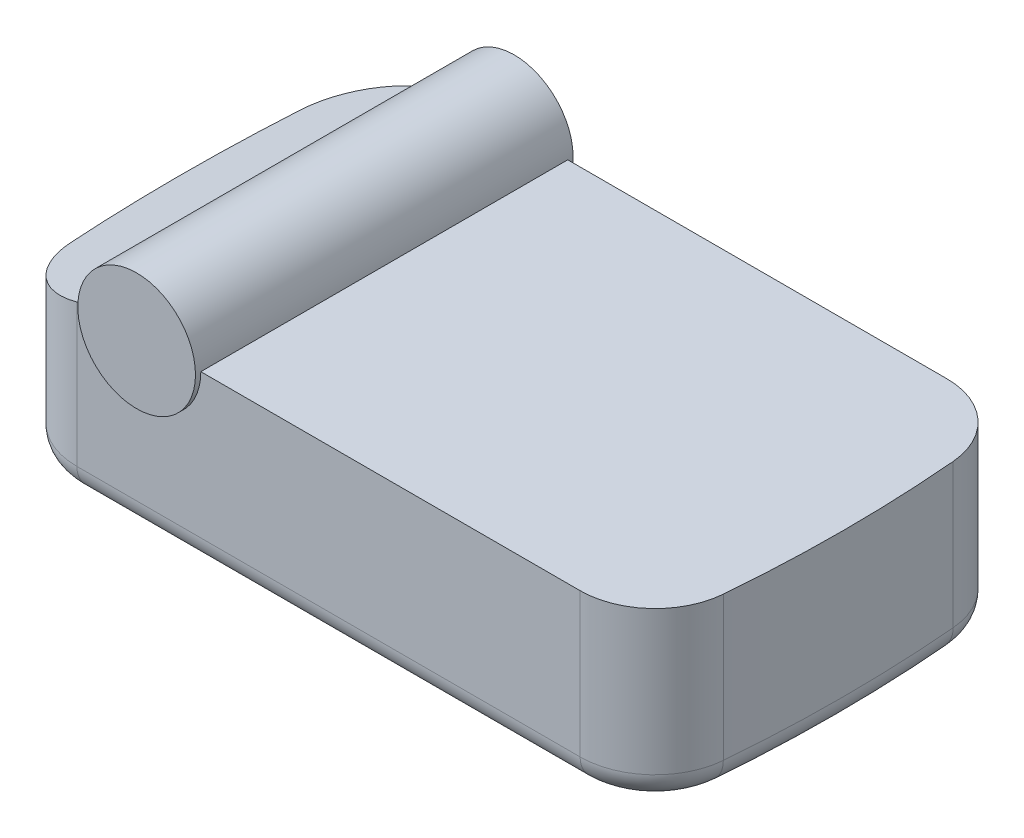
SolidWorks part; units mm, degrees
ref_plane "Front Plane" through (0, 0, 0) normal (0, 0, 1) x (1, 0, 0)
ref_plane "Top Plane" through (0, 0, 0) normal (0, 1, 0) x (1, 0, 0)
ref_plane "Right Plane" through (0, 0, 0) normal (1, 0, 0) x (0, 0, -1)
sketch "Sketch1" plane through (0, 0, 0) normal (0, 1, 0) x (1, 0, 0)
  line L0 (-29.7867, 17.15) -> (-29.7867, -17.15) construction
  line L1 (-23.52, 17.15) -> (23.52, 17.15)
  line L3 (-23.52, -17.15) -> (23.52, -17.15)
  line L5 (-29.7867, 17.15) -> (29.7867, -17.15) construction
  line L6 (-29.7867, -17.15) -> (29.7867, 17.15) construction
  line L7 (29.7867, 17.15) -> (29.7867, -17.15) construction
  arc A0 (-30.4949, 10.7421) -> (-30.4949, -10.7421) centre (96.05, 0) ccw
  arc A1 (30.4949, 10.7421) -> (30.4949, -10.7421) centre (-96.05, 0) cw
  arc A2 (23.52, 17.15) -> (30.4949, 10.7421) centre (23.52, 10.15) cw
  arc A3 (23.52, -17.15) -> (30.4949, -10.7421) centre (23.52, -10.15) ccw
  arc A4 (-30.4949, -10.7421) -> (-23.52, -17.15) centre (-23.52, -10.15) ccw
  arc A5 (-23.52, 17.15) -> (-30.4949, 10.7421) centre (-23.52, 10.15) ccw
  point P0 (0, 0)
  point P8 (-30.95, 0)
  point P9 (30.95, 0)
  dimension "D3" = 127
  dimension "D1" = 7
  dimension "D2" = 34.3
  dimension "D4" = 61.9
extrude "Boss-Extrude1" add sketch "Sketch1" along normal blind 16
fillet "Fillet1" radius 2.54 8 edges at (0, 0, 17.15) (0, 0, -17.15) (30.95, 0, 0) (-30.95, 0, 0) (-28.2558, 0, -15.3048) (28.2558, 0, -15.3048) (28.2558, 0, 15.3048) (-28.2558, 0, 15.3048)
sketch "Sketch3" plane through (0, 0, 17.15) normal (0, 0, 1) x (1, 0, 0)
  line L2 (-29.7867, 16) -> (-29.7867, 2.54) construction
  line L4 (-23.52, 16) -> (23.52, 16) construction
  circle A0 centre (-17.439, 16) radius 5.5
  dimension "D1" = 11
  dimension "D2" = 12.3477
extrude "Boss-Extrude2" add sketch "Sketch3" along normal blind 0.5 and the other way offset from surface (34.8 mm away) 0.5 other way up to face at (0, 9.27, -17.15)
ref_plane "Plane1" through (30.95, 0, 0) normal (1, 0, 0) x (0, 0, -1)
sketch "Sketch5" plane through (0, 0, 17.15) normal (0, 0, 1) x (1, 0, 0)
  line L0 (-22.939, 16) -> (-30.95, 13.8535)
  line L3 (-30.95, 16) -> (-22.939, 16)
  line L4 (-30.95, 16) -> (-30.95, 2.54) construction
  line L5 (-30.95, 13.8535) -> (-30.95, 16)
  dimension "D1" = 15
extrude "Cut-Extrude2" cut sketch "Sketch5" against normal through all
